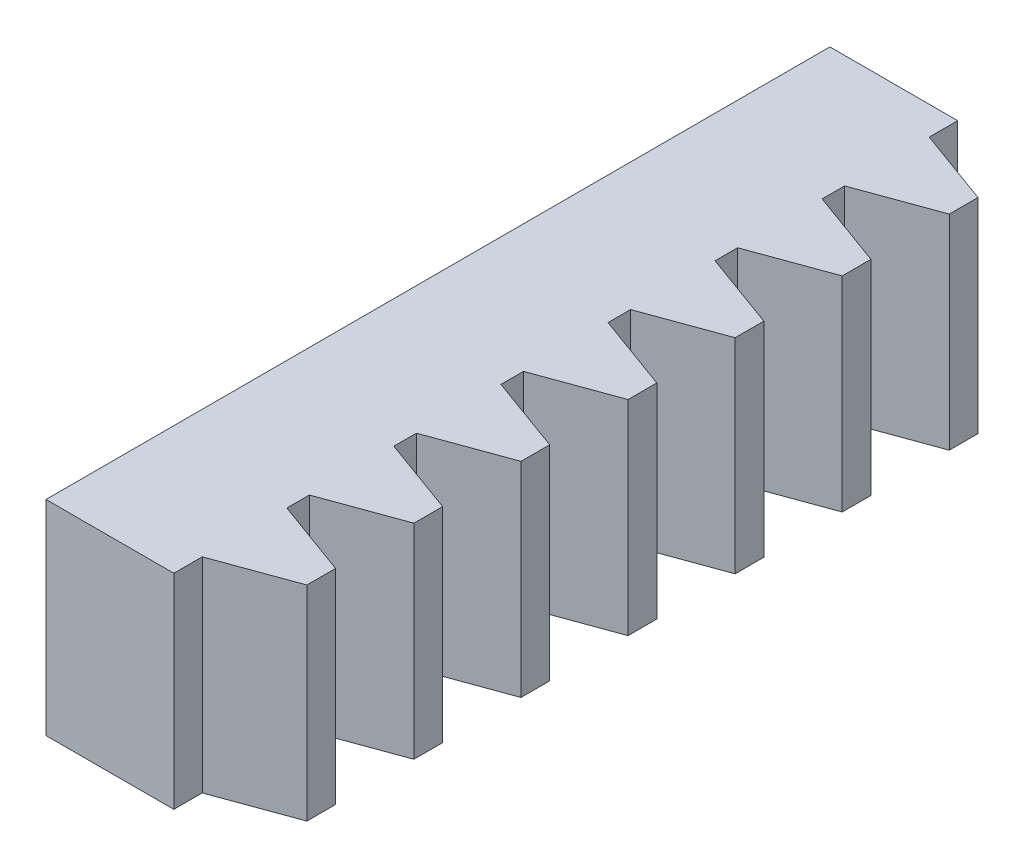
SolidWorks part; units mm, degrees
material "Galvanized Steel"
ref_plane "Front Plane" through (0, 0, 0) normal (0, 0, 1) x (1, 0, 0)
ref_plane "Top Plane" through (0, 0, 0) normal (0, 1, 0) x (1, 0, 0)
ref_plane "Right Plane" through (0, 0, 0) normal (1, 0, 0) x (0, 0, -1)
sketch "Sketch10" plane through (0, 0, 0) normal (0, 0, 1) x (1, 0, 0)
  line L1 (-3, -3) -> (3, -3)
  line L2 (-3, -3) -> (-3, 3)
  line L3 (-3, 3) -> (3, 3)
  line L4 (3, -3) -> (3, 3)
extrude "RACK_BAR" add sketch "Sketch10" along normal mid plane 23
sketch "Sketch12" plane through (0, 0, 0) normal (0, 1, 0) x (1, 0, 0)
  line L0 (0.75, -12) -> (3.5, -12)
  line L1 (3.5, -12) -> (3.5, 12)
  line L2 (3.5, 12) -> (0.75, 12)
  line L3 (0.75, 12) -> (0.75, -12)
extrude "RACK_ROOT_STEP" cut sketch "Sketch12" against normal through all and the other way through all
sketch "Sketch13" plane through (0, 0, 0) normal (0, 1, 0) x (1, 0, 0)
  line L0 (0.5, 1.3314) -> (3, 0.4214)
  line L1 (3, 0.4214) -> (3, -0.4214)
  line L2 (3, -0.4214) -> (0.5, -1.3314)
  line L3 (0.5, -1.3314) -> (0.5, 1.3314)
  line L4 (0.5, 4.473) -> (3, 3.563)
  line L5 (3, 3.563) -> (3, 2.7202)
  line L6 (3, 2.7202) -> (0.5, 1.8102)
  line L7 (0.5, 1.8102) -> (0.5, 4.473)
  line L8 (0.5, -1.8102) -> (3, -2.7202)
  line L9 (3, -2.7202) -> (3, -3.563)
  line L10 (3, -3.563) -> (0.5, -4.473)
  line L11 (0.5, -4.473) -> (0.5, -1.8102)
  line L12 (0.5, 7.6146) -> (3, 6.7046)
  line L13 (3, 6.7046) -> (3, 5.8618)
  line L14 (3, 5.8618) -> (0.5, 4.9518)
  line L15 (0.5, 4.9518) -> (0.5, 7.6146)
  line L16 (0.5, -4.9518) -> (3, -5.8618)
  line L17 (3, -5.8618) -> (3, -6.7046)
  line L18 (3, -6.7046) -> (0.5, -7.6146)
  line L19 (0.5, -7.6146) -> (0.5, -4.9518)
  line L20 (0.5, 10.7562) -> (3, 9.8462)
  line L21 (3, 9.8462) -> (3, 9.0034)
  line L22 (3, 9.0034) -> (0.5, 8.0934)
  line L23 (0.5, 8.0934) -> (0.5, 10.7562)
  line L24 (0.5, -8.0934) -> (3, -9.0034)
  line L25 (3, -9.0034) -> (3, -9.8462)
  line L26 (3, -9.8462) -> (0.5, -10.7562)
  line L27 (0.5, -10.7562) -> (0.5, -8.0934)
extrude "RACK_TEETH" add sketch "Sketch13" along normal mid plane 6
sketch "Sketch15" plane through (0, 0, -11.5) normal (0, 0, -1) x (-1, 0, 0)
  line L0 (-0.75, 3) -> (3, 3) construction
  line L1 (3, 3) -> (3, -3) construction
  circle A0 centre (1.25, 0) radius 1.0013
  dimension "D3" = 2.0026
  dimension "D1" = 3
  dimension "D2" = 1.75
extrude "Cut-Extrude2" cut sketch "Sketch15" against normal blind 4.5
